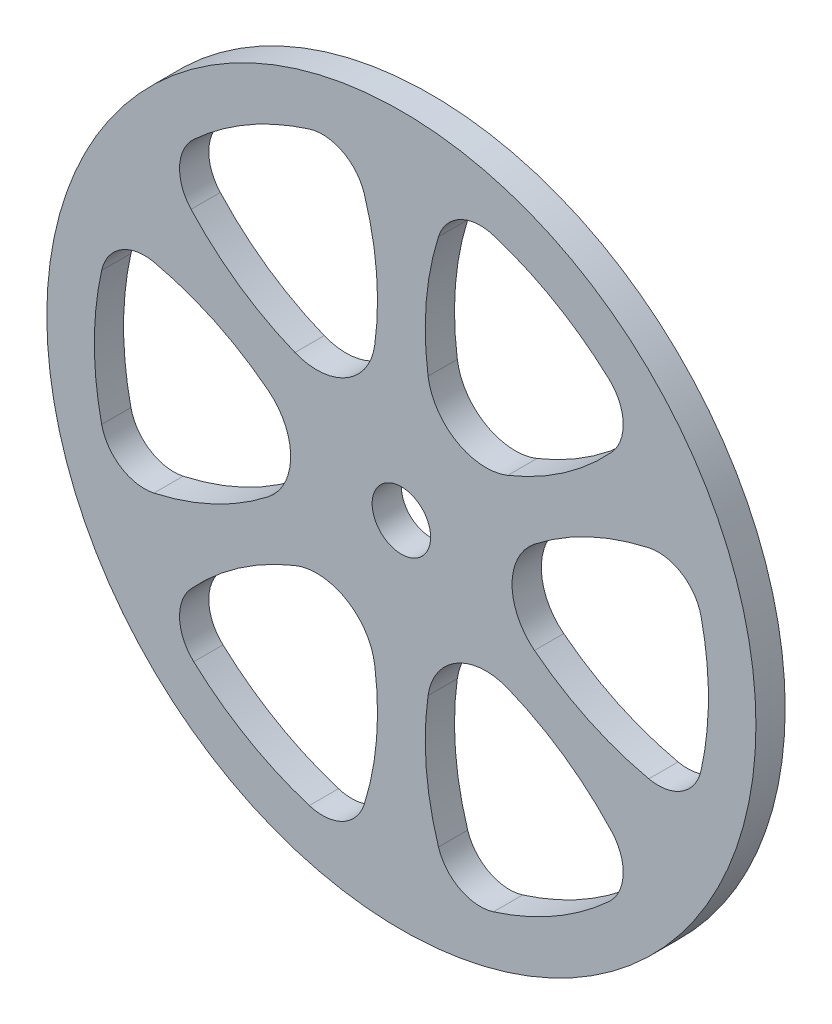
SolidWorks part; units mm, degrees
ref_plane "前视基准面" through (0, 0, 0) normal (0, 0, 1) x (1, 0, 0)
ref_plane "上视基准面" through (0, 0, 0) normal (0, 1, 0) x (1, 0, 0)
ref_plane "右视基准面" through (0, 0, 0) normal (1, 0, 0) x (0, 0, -1)
sketch "Model" plane through (0, 0, 0) normal (0, 0, 1) x (1, 0, 0)
  circle A0 centre (1461.028, 726.3144) radius 24.25
  circle A1 centre (1461.028, 726.3144) radius 2
  arc A2 (1454.7305, 746.3479) -> (1446.8272, 741.7849) centre (1461.028, 726.3144) ccw
  arc A3 (1446.6427, 737.5495) -> (1453.75, 732.6235) centre (1461.028, 750.7144) ccw
  arc A4 (1446.8272, 741.7849) -> (1446.6427, 737.5495) centre (1448.8559, 739.5749) ccw
  arc A5 (1459.2031, 735.7719) -> (1458.4907, 744.3899) centre (1439.897, 738.5144) ccw
  arc A6 (1458.4907, 744.3899) -> (1454.7305, 746.3479) centre (1455.6301, 743.486) ccw
  arc A7 (1453.75, 732.6235) -> (1459.2031, 735.7719) centre (1455.2429, 736.3345) ccw
  arc A8 (1440.5297, 730.8774) -> (1440.5297, 721.7514) centre (1461.028, 726.3144) ccw
  arc A9 (1444.1055, 719.474) -> (1451.9251, 723.166) centre (1439.897, 738.5144) ccw
  arc A10 (1440.5297, 721.7514) -> (1444.1055, 719.474) centre (1443.458, 722.4033) ccw
  arc A11 (1451.9251, 729.4628) -> (1444.1055, 733.1549) centre (1439.897, 714.1144) ccw
  arc A12 (1444.1055, 733.1549) -> (1440.5297, 730.8774) centre (1443.458, 730.2256) ccw
  arc A13 (1451.9251, 723.166) -> (1451.9251, 729.4628) centre (1449.4578, 726.3144) ccw
  arc A14 (1446.8272, 710.8439) -> (1454.7305, 706.2809) centre (1461.028, 726.3144) ccw
  arc A15 (1458.4907, 708.2389) -> (1459.2031, 716.8569) centre (1439.897, 714.1144) ccw
  arc A16 (1454.7305, 706.2809) -> (1458.4907, 708.2389) centre (1455.6301, 709.1428) ccw
  arc A17 (1453.75, 720.0053) -> (1446.6427, 715.0793) centre (1461.028, 701.9144) ccw
  arc A18 (1446.6427, 715.0793) -> (1446.8272, 710.8439) centre (1448.8559, 713.054) ccw
  arc A19 (1459.2031, 716.8569) -> (1453.75, 720.0053) centre (1455.2429, 716.2944) ccw
  arc A20 (1467.3254, 706.2809) -> (1475.2288, 710.8439) centre (1461.028, 726.3144) ccw
  arc A21 (1475.4132, 715.0793) -> (1468.306, 720.0053) centre (1461.028, 701.9144) ccw
  arc A22 (1475.2288, 710.8439) -> (1475.4132, 715.0793) centre (1473.2001, 713.054) ccw
  arc A23 (1462.8528, 716.8569) -> (1463.5652, 708.2389) centre (1482.159, 714.1144) ccw
  arc A24 (1463.5652, 708.2389) -> (1467.3254, 706.2809) centre (1466.4258, 709.1428) ccw
  arc A25 (1468.306, 720.0053) -> (1462.8528, 716.8569) centre (1466.8131, 716.2944) ccw
  arc A26 (1481.5262, 721.7514) -> (1481.5262, 730.8774) centre (1461.028, 726.3144) ccw
  arc A27 (1477.9505, 733.1549) -> (1470.1308, 729.4628) centre (1482.159, 714.1144) ccw
  arc A28 (1481.5262, 730.8774) -> (1477.9505, 733.1549) centre (1478.5979, 730.2256) ccw
  arc A29 (1470.1308, 723.166) -> (1477.9505, 719.474) centre (1482.159, 738.5144) ccw
  arc A30 (1477.9505, 719.474) -> (1481.5262, 721.7514) centre (1478.5979, 722.4033) ccw
  arc A31 (1470.1308, 729.4628) -> (1470.1308, 723.166) centre (1472.5981, 726.3144) ccw
  arc A32 (1475.2288, 741.7849) -> (1467.3254, 746.3479) centre (1461.028, 726.3144) ccw
  arc A33 (1463.5652, 744.3899) -> (1462.8528, 735.7719) centre (1482.159, 738.5144) ccw
  arc A34 (1467.3254, 746.3479) -> (1463.5652, 744.3899) centre (1466.4258, 743.486) ccw
  arc A35 (1468.306, 732.6235) -> (1475.4132, 737.5495) centre (1461.028, 750.7144) ccw
  arc A36 (1475.4132, 737.5495) -> (1475.2288, 741.7849) centre (1473.2001, 739.5749) ccw
  arc A37 (1462.8528, 735.7719) -> (1468.306, 732.6235) centre (1466.8131, 736.3345) ccw
  dimension "D1" = 48.5
extrude "凸台-拉伸1" add sketch "Model" along normal blind 2
